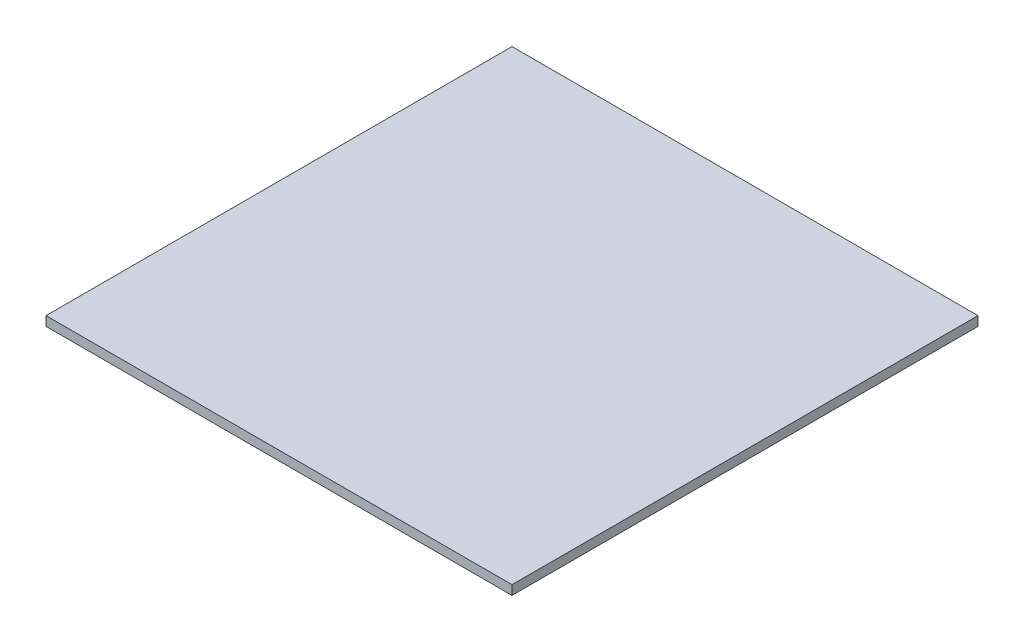
SolidWorks part; units mm, degrees
ref_plane "Front" through (0, 0, 0) normal (0, 0, 1) x (1, 0, 0)
ref_plane "Top" through (0, 0, 0) normal (0, 1, 0) x (1, 0, 0)
ref_plane "Right" through (0, 0, 0) normal (1, 0, 0) x (0, 0, -1)
sketch "Sketch1" plane through (0, 0, 0) normal (0, 1, 0) x (1, 0, 0)
  line L0 (-50, 0) -> (50, 0) construction
  line L1 (-40, 40) -> (40, 40)
  line L2 (-40, 40) -> (-40, -40)
  line L3 (-40, -40) -> (40, -40)
  line L4 (40, 40) -> (40, -40)
  line L5 (-40, 40) -> (40, -40) construction
  line L6 (-40, -40) -> (40, 40) construction
  line L7 (0, -50) -> (0, 50) construction
  point P0 (0, 0)
  point P5 (0, 0)
  point P6 (0, 0)
  point P9 (0, 0)
  dimension "D1" = 80
  dimension "D2" = 80
extrude "PCB BASE" add sketch "Sketch1" along normal blind 1.6
